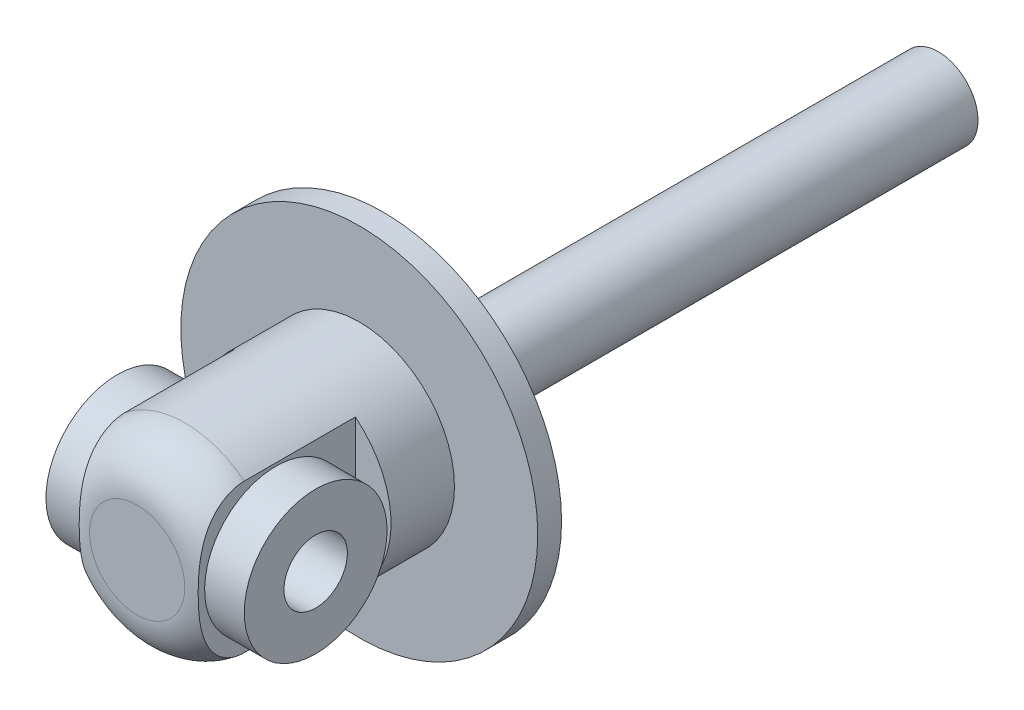
SolidWorks part; units mm, degrees
ref_plane "Piano frontale" through (0, 0, 0) normal (0, 0, 1) x (1, 0, 0)
ref_plane "Piano superiore" through (0, 0, 0) normal (0, 1, 0) x (1, 0, 0)
ref_plane "Piano destro" through (0, 0, 0) normal (1, 0, 0) x (0, 0, -1)
sketch "Schizzo1" plane through (0, 0, 0) normal (0, 0, 1) x (1, 0, 0)
  circle A0 centre (0, 0) radius 5
  dimension "D1" = 10
extrude "Estrusione-Estrusione1" add sketch "Schizzo1" along normal blind 70
sketch "Schizzo2" plane through (0, 0, 70) normal (0, 0, 1) x (1, 0, 0)
  circle A0 centre (0, 0) radius 22.5
  dimension "D1" = 45
extrude "Estrusione-Estrusione2" add sketch "Schizzo2" along normal blind 3
sketch "Schizzo3" plane through (0, 0, 73) normal (0, 0, 1) x (1, 0, 0)
  circle A0 centre (0, 0) radius 12
  dimension "D1" = 24
extrude "Estrusione-Estrusione3" add sketch "Schizzo3" along normal blind 28
fillet "Raccordo1" radius 6 1 edges at (12, 0, 101)
sketch "Schizzo4" plane through (0, 0, 101) normal (0, 0, 1) x (1, 0, 0)
  line L0 (0, 22.5) -> (0, -22.5) construction
  line L1 (-21.7464, 0) -> (23.0974, 0) construction
  line L2 (7.5, -15) -> (17.5, -15)
  line L3 (7.5, -15) -> (7.5, 15)
  line L4 (7.5, 15) -> (17.5, 15)
  line L5 (17.5, -15) -> (17.5, 15)
  line L6 (7.5, -15) -> (17.5, 15) construction
  line L7 (7.5, 15) -> (17.5, -15) construction
  circle A0 centre (0, 0) radius 22.5 construction
  point P5 (12.5, 0)
  dimension "D1" = 30
  dimension "D2" = 10
  dimension "D3" = 7.5
extrude "Taglio-Estrusione1" cut sketch "Schizzo4" against normal blind 20
mirror "Specchia1" about plane through (0, 0, 0) normal (1, 0, 0) of "Taglio-Estrusione1"
sketch "Schizzo7" plane through (7.5, 0, 0) normal (1, 0, 0) x (0, 0, -1)
  line L0 (-91, 21.4011) -> (-91, -28.1698) construction
  line L1 (-73, 22.5) -> (-73, -22.5) construction
  line L2 (0, 0) -> (-133.1458, 0) construction
  circle A0 centre (-91, 0) radius 9
  dimension "D2" = 18
  dimension "D1" = 18
extrude "Estrusione-Estrusione4" add sketch "Schizzo7" along normal blind 5
mirror "Specchia2" about plane through (0, 0, 0) normal (1, 0, 0) of "Estrusione-Estrusione4"
sketch "Schizzo8" plane through (12.5, 0, 0) normal (1, 0, 0) x (0, 0, -1)
  line L0 (0, 0) -> (-108.3586, 0) construction
  line L1 (-91, 19.1296) -> (-91, -35.8401) construction
  line L2 (-73, 22.5) -> (-73, -22.5) construction
  circle A0 centre (-91, 0) radius 4
  dimension "D2" = 8
  dimension "D1" = 18
extrude "Taglio-Estrusione3" cut sketch "Schizzo8" against normal blind 25
